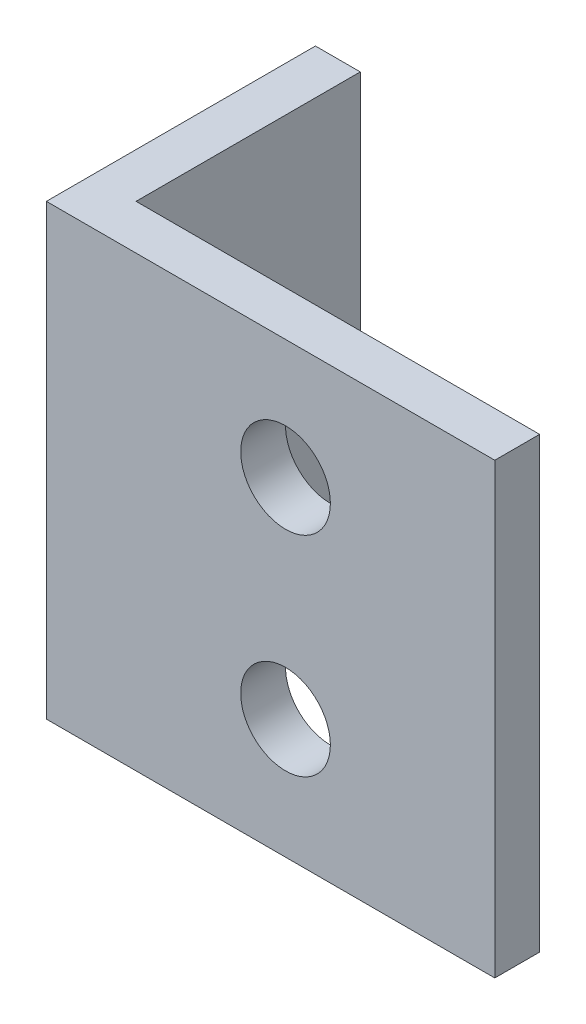
SolidWorks part; units mm, degrees
ref_plane "Plan de face" through (0, 0, 0) normal (0, 0, 1) x (1, 0, 0)
ref_plane "Plan de dessus" through (0, 0, 0) normal (0, 1, 0) x (1, 0, 0)
ref_plane "Plan de droite" through (0, 0, 0) normal (1, 0, 0) x (0, 0, -1)
sketch "Esquisse1" plane through (0, 0, 0) normal (0, 1, 0) x (1, 0, 0)
  line L0 (-33.0198, 0) -> (-33.0198, 9)
  line L1 (-33.0198, 9) -> (-31.5198, 9)
  line L2 (-31.5198, 9) -> (-31.5198, 1.5)
  line L3 (-31.5198, 1.5) -> (-18.0198, 1.5)
  line L4 (-18.0198, 1.5) -> (-18.0198, 0)
  line L5 (-18.0198, 0) -> (-33.0198, 0)
  dimension "D1" = 1.5
  dimension "D2" = 1.5
  dimension "D3" = 9
  dimension "D4" = 15
extrude "Extrusion1" add sketch "Esquisse1" along normal blind 15
sketch "Esquisse2" plane through (0, 0, 0) normal (0, 0, 1) x (1, 0, 0)
  line L0 (-18.0198, 15) -> (-18.0198, 0) construction
  line L1 (-33.0198, 15) -> (-18.0198, 15) construction
  line L2 (-33.0198, 0) -> (-18.0198, 0) construction
  circle A0 centre (-25.0198, 11) radius 1.5
  circle A1 centre (-25.0198, 4) radius 1.5
  dimension "D1" = 7
  dimension "D3" = 4
  dimension "D2" = 4
  dimension "D4" = 7
extrude "Extrusion2" cut sketch "Esquisse2" against normal blind 15
